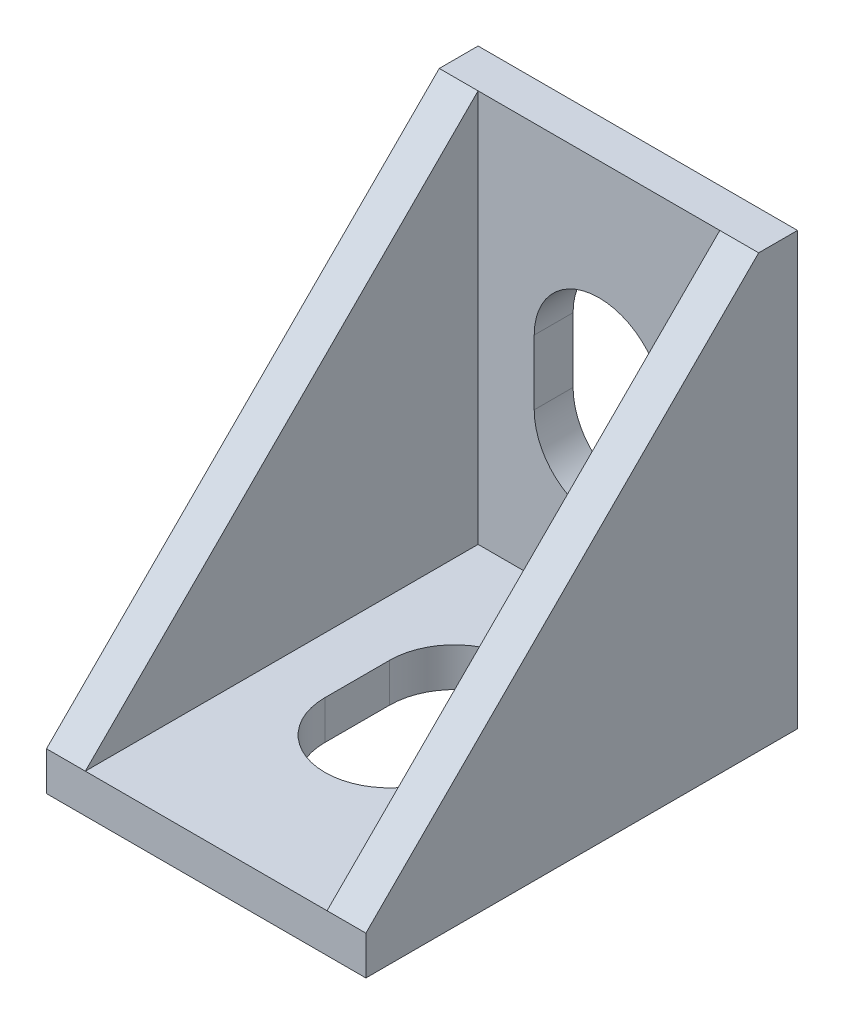
SolidWorks part; units mm, degrees
ref_plane "Front Plane" through (0, 0, 0) normal (0, 0, 1) x (1, 0, 0)
ref_plane "Top Plane" through (0, 0, 0) normal (0, 1, 0) x (1, 0, 0)
ref_plane "Right Plane" through (0, 0, 0) normal (1, 0, 0) x (0, 0, -1)
sketch "Sketch1" plane through (0, 0, 0) normal (0, 1, 0) x (1, 0, 0)
  line L1 (0, 0) -> (14.8, 0)
  line L2 (0, 0) -> (0, -20)
  line L3 (0, -20) -> (14.8, -20)
  line L4 (14.8, 0) -> (14.8, -20)
extrude "Boss-Extrude1" add sketch "Sketch1" along normal blind 1.8 contours L1 L4 L3 L2
sketch "Sketch2" plane through (0, 1.8, 0) normal (0, 1, 0) x (1, 0, 0)
  line L0 (14.8, 0) -> (14.8, -20) construction
  line L1 (0, 0) -> (14.8, 0)
  line L2 (0, 0) -> (0, -1.8)
  line L3 (0, -1.8) -> (14.8, -1.8)
  line L4 (14.8, 0) -> (14.8, -1.8)
extrude "Boss-Extrude2" add sketch "Sketch2" along normal blind 18.2
sketch "Sketch3" plane through (0, 0, 0) normal (0, -1, 0) x (1, 0, 0)
  line L0 (0, 20) -> (14.8, 0) construction
  line L1 (0, 0) -> (14.8, 20) construction
  line L2 (7.4, 11.5) -> (7.4, 8.5) construction
  line L3 (10.4, 11.5) -> (10.4, 8.5)
  line L4 (4.4, 11.5) -> (4.4, 8.5)
  arc A0 (10.4, 11.5) -> (4.4, 11.5) centre (7.4, 11.5) ccw
  arc A1 (4.4, 8.5) -> (10.4, 8.5) centre (7.4, 8.5) ccw
  point P10 (7.4, 10)
extrude "Cut-Extrude2" cut sketch "Sketch3" against normal through all
sketch "Sketch5" plane through (0, 0, 0) normal (0, 0, -1) x (-1, 0, 0)
  line L0 (-14.8, 20) -> (0, 0) construction
  line L1 (-14.8, 0) -> (0, 20) construction
  line L2 (-7.4, 11.5) -> (-7.4, 8.5) construction
  line L3 (-4.4, 11.5) -> (-4.4, 8.5)
  line L4 (-10.4, 11.5) -> (-10.4, 8.5)
  arc A0 (-4.4, 11.5) -> (-10.4, 11.5) centre (-7.4, 11.5) ccw
  arc A1 (-10.4, 8.5) -> (-4.4, 8.5) centre (-7.4, 8.5) ccw
  point P10 (-7.4, 10)
extrude "Cut-Extrude3" cut sketch "Sketch5" against normal blind 17.2
sketch "Sketch6" plane through (0, 0, 0) normal (-1, 0, 0) x (0, 0, 1)
  line L0 (1.8, 20) -> (1.8, 1.8)
  line L1 (1.8, 1.8) -> (20, 1.8)
  line L2 (20, 1.8) -> (1.8, 20)
extrude "Boss-Extrude3" add sketch "Sketch6" against normal blind 1.8
sketch "Sketch7" plane through (14.8, 0, 0) normal (1, 0, 0) x (0, 0, -1)
  line L0 (-1.8, 20) -> (-1.8, 1.8)
  line L1 (-1.8, 1.8) -> (-20, 1.8)
  line L2 (-20, 1.8) -> (-1.8, 20)
extrude "Boss-Extrude4" add sketch "Sketch7" against normal blind 1.8
